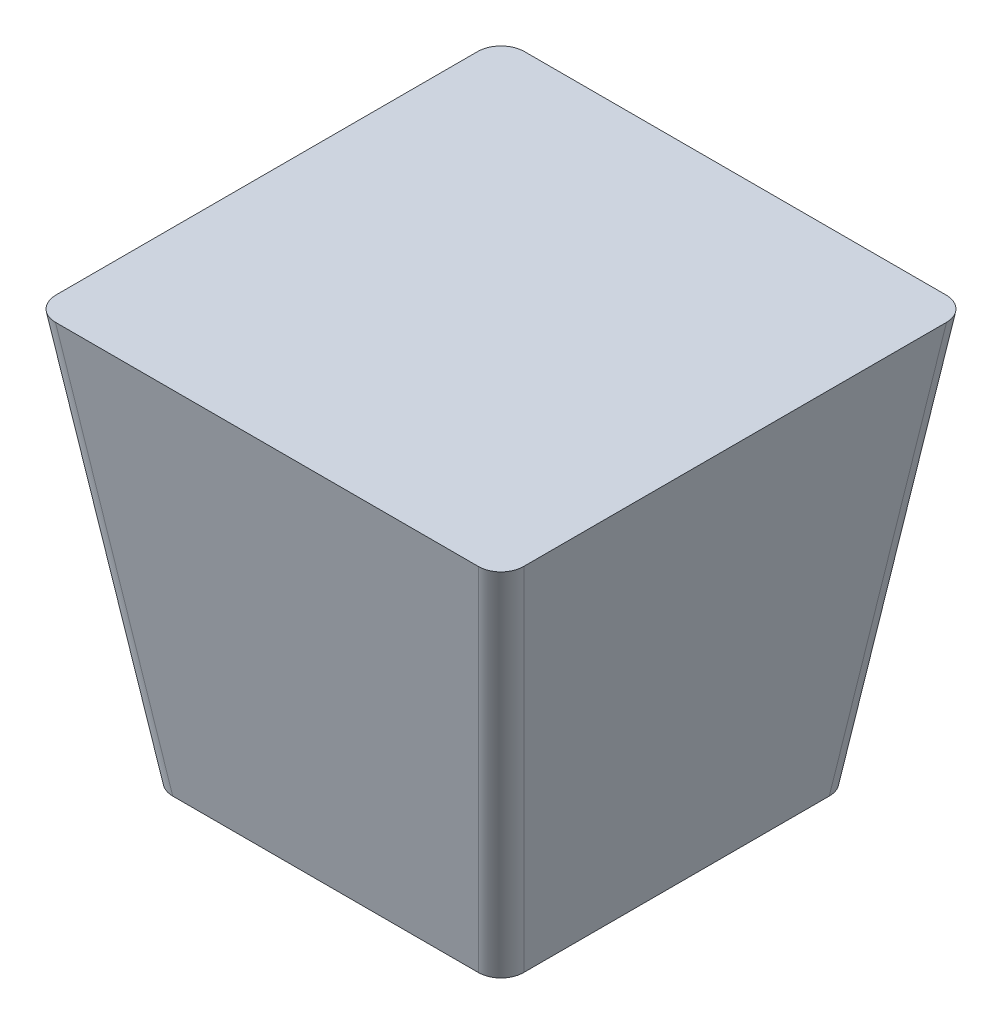
SolidWorks part; units mm, degrees
ref_plane "Спереди" through (0, 0, 0) normal (0, 0, 1) x (1, 0, 0)
ref_plane "Сверху" through (0, 0, 0) normal (0, 1, 0) x (1, 0, 0)
ref_plane "Справа" through (0, 0, 0) normal (1, 0, 0) x (0, 0, -1)
sketch "Эскиз1" plane through (0, 0, 0) normal (0, 1, 0) x (1, 0, 0)
  line L1 (-50.8078, 15.5432) -> (-10.8078, 15.5432)
  line L2 (-50.8078, 15.5432) -> (-50.8078, -24.4568)
  line L3 (-50.8078, -24.4568) -> (-10.8078, -24.4568)
  line L4 (-10.8078, 15.5432) -> (-10.8078, -24.4568)
  dimension "D1" = 40
  dimension "D2" = 40
extrude "Бобышка-Вытянуть1" add sketch "Эскиз1" along normal blind 40
sketch "Эскиз2" plane through (0, 0, -15.5432) normal (0, 0, -1) x (-1, 0, 0)
  line L0 (10.8078, 40) -> (10.8078, 0)
  line L1 (10.8078, 0) -> (20.8078, 0)
  line L2 (10.8078, 0) -> (50.8078, 0) construction
  line L3 (20.8078, 0) -> (10.8078, 40)
  dimension "D1" = 10
extrude "Вырез-Вытянуть1" cut sketch "Эскиз2" against normal through all
sketch "Эскиз3" plane through (-50.8078, 0, 0) normal (-1, 0, 0) x (0, 0, 1)
  line L0 (24.4568, 0) -> (14.4568, 0)
  line L1 (-15.5432, 0) -> (24.4568, 0) construction
  line L2 (14.4568, 0) -> (24.4568, 40)
  line L3 (24.4568, 40) -> (24.4568, 0)
  dimension "D1" = 10
extrude "Вырез-Вытянуть2" cut sketch "Эскиз3" against normal through all
fillet "Скругление1" radius 2 4 edges at (-50.8078, 20, 19.4568) (-15.8078, 20, 19.4568) (-15.8078, 20, -15.5432) (-50.8078, 20, -15.5432)
